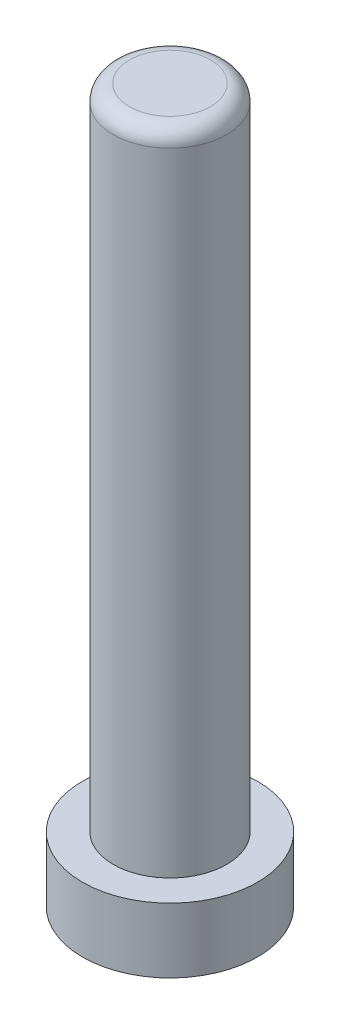
SolidWorks part; units mm, degrees
ref_plane "Front Plane" through (0, 0, 0) normal (0, 0, 1) x (1, 0, 0)
ref_plane "Top Plane" through (0, 0, 0) normal (0, 1, 0) x (1, 0, 0)
ref_plane "Right Plane" through (0, 0, 0) normal (1, 0, 0) x (0, 0, -1)
sketch "Sketch1" plane through (0, 0, 0) normal (0, 1, 0) x (1, 0, 0)
  line L1 (-2.8, -2.7) -> (2.8, -2.7) construction
  line L2 (-2.8, -2.7) -> (-2.8, 2.7) construction
  line L3 (-2.8, 2.7) -> (2.8, 2.7) construction
  line L4 (2.8, -2.7) -> (2.8, 2.7) construction
  line L5 (-2.8, -2.7) -> (2.8, 2.7) construction
  line L6 (-2.8, 2.7) -> (2.8, -2.7) construction
  circle A0 centre (0, 0) radius 2.7
  point P0 (0, 0)
  dimension "D1" = 5.6
  dimension "D2" = 5.4
extrude "Boss-Extrude1" add sketch "Sketch1" along normal blind 2
sketch "Sketch2" plane through (0, 2, 0) normal (0, 1, 0) x (1, 0, 0)
  circle A0 centre (0, 0) radius 1.75
  dimension "D1" = 3.5
sketch "Sketch3" plane through (0, 0, 0) normal (0, -1, 0) x (1, 0, 0)
  circle A0 centre (0, 0) radius 1.2
  circle A1 centre (0, 0) radius 0.95
  point P0 (0, 0)
  dimension "D1" = 2.4
  dimension "D2" = 1.9
extrude "Cut-Extrude2" cut sketch "Sketch3" against normal blind 9.5 contours A1
sketch "Sketch7" plane through (0, 0, 0) normal (0, -1, 0) x (1, 0, 0)
  circle A0 centre (0, 0) radius 1.2
  dimension "D1" = 2.4
extrude "Cut-Extrude4" cut sketch "Sketch7" against normal blind 2.8
extrude "Boss-Extrude2" add sketch "Sketch2" along normal blind 20
fillet "Fillet2" radius 0.5 1 edges at (0, 22, 1.75)
sketch "Sketch8" plane through (0, 0, 0) normal (0, -1, 0) x (1, 0, 0)
  circle A0 centre (0, 0) radius 0.95
  dimension "D1" = 1.9
extrude "Cut-Extrude5" cut sketch "Sketch8" against normal blind 9.5
